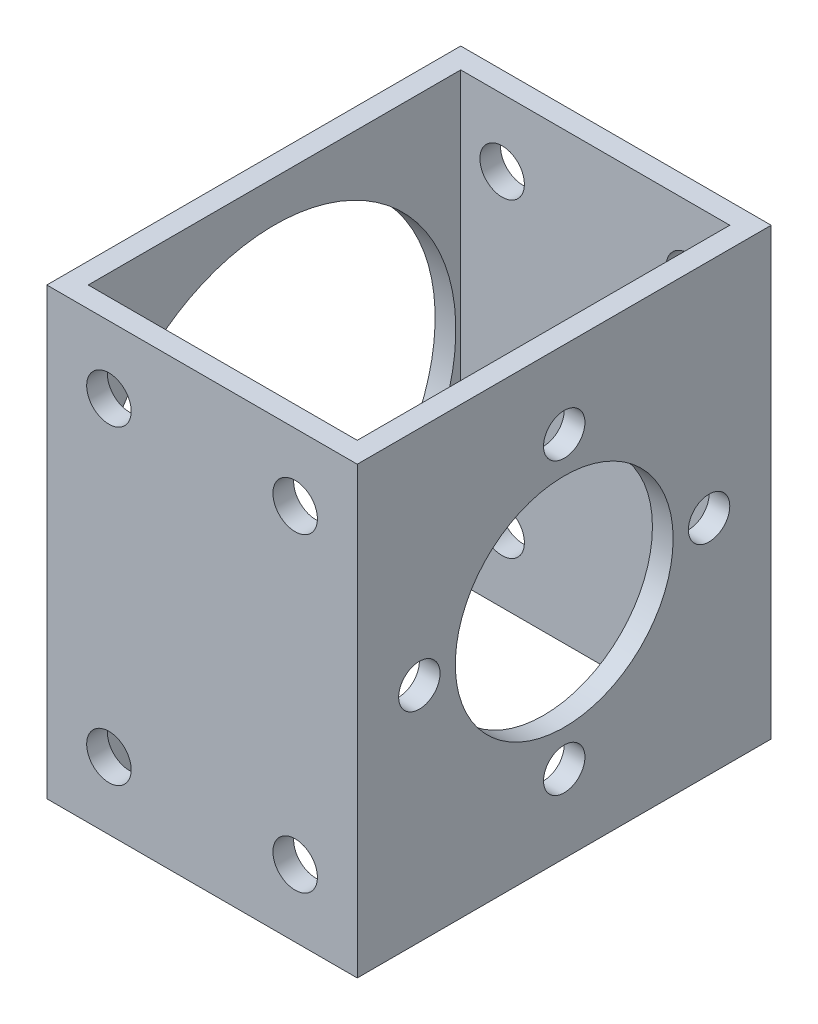
SolidWorks part; units mm, degrees
material "1060 合金"
ref_plane "前视基准面" through (0, 0, 0) normal (0, 0, 1) x (1, 0, 0)
ref_plane "上视基准面" through (0, 0, 0) normal (0, 1, 0) x (1, 0, 0)
ref_plane "右视基准面" through (0, 0, 0) normal (1, 0, 0) x (0, 0, -1)
sketch "草图1" plane through (0, 0, 0) normal (0, 1, 0) x (1, 0, 0)
  line L0 (2, -2) -> (28, -2)
  line L1 (0, 0) -> (30, 0)
  line L2 (0, 0) -> (0, -40)
  line L3 (0, -40) -> (30, -40)
  line L4 (30, 0) -> (30, -40)
  line L5 (28, -2) -> (28, -38)
  line L6 (2, -38) -> (28, -38)
  line L7 (2, -2) -> (2, -38)
  dimension "D1" = 30
  dimension "D2" = 40
  dimension "D3" = 2
extrude "凸台-拉伸1" add sketch "草图1" along normal blind 43
sketch "草图2" plane through (0, 0, 0) normal (0, 0, -1) x (-1, 0, 0)
  line L0 (0, 43) -> (0, 0) construction
  line L1 (-30, 0) -> (0, 0) construction
  line L2 (-30, 43) -> (-30, 0) construction
  line L3 (-30, 43) -> (0, 43) construction
  circle A0 centre (-6, 6.5) radius 2.15
  circle A1 centre (-24, 6.5) radius 2.15
  circle A2 centre (-24, 36.5) radius 2.15
  circle A3 centre (-6, 36.5) radius 2.15
  dimension "D1" = 4.3
  dimension "D2" = 6
  dimension "D3" = 6.5
  dimension "D4" = 6
  dimension "D5" = 6.5
  dimension "D6" = 6
  dimension "D7" = 6.5
  dimension "D8" = 6
  dimension "D9" = 6.5
extrude "切除-拉伸1" cut sketch "草图2" against normal through all
sketch "草图3" plane through (0, 0, 0) normal (-1, 0, 0) x (0, 0, 1)
  line L0 (0, 43) -> (0, 0) construction
  line L3 (0, 43) -> (40, 43) construction
  circle A0 centre (20, 21.5) radius 17.525
  dimension "D1" = 35.05
  dimension "D2" = 20
  dimension "D3" = 21.5
extrude "切除-拉伸2" cut sketch "草图3" against normal up to next
sketch "草图4" plane through (30, 0, 0) normal (1, 0, 0) x (0, 0, -1)
  line L0 (0, 43) -> (0, 0) construction
  line L1 (-40, 0) -> (0, 0) construction
  line L2 (-20, 21.5) -> (0, 21.5) construction
  line L3 (-20, 21.5) -> (-20, 0.2254) construction
  circle A0 centre (-20, 21.5) radius 10.525
  circle A1 centre (-6, 21.5) radius 2
  circle A2 centre (-20, 7.5) radius 2
  circle A3 centre (-34, 21.5) radius 2
  circle A4 centre (-20, 35.5) radius 2
  dimension "D1" = 21.05
  dimension "D4" = 4
  dimension "D2" = 20
  dimension "D3" = 21.5
  dimension "D5" = 28
  dimension "D6" = 28
  dimension "D7" = 14
  dimension "D8" = 14
extrude "切除-拉伸3" cut sketch "草图4" against normal up to next
